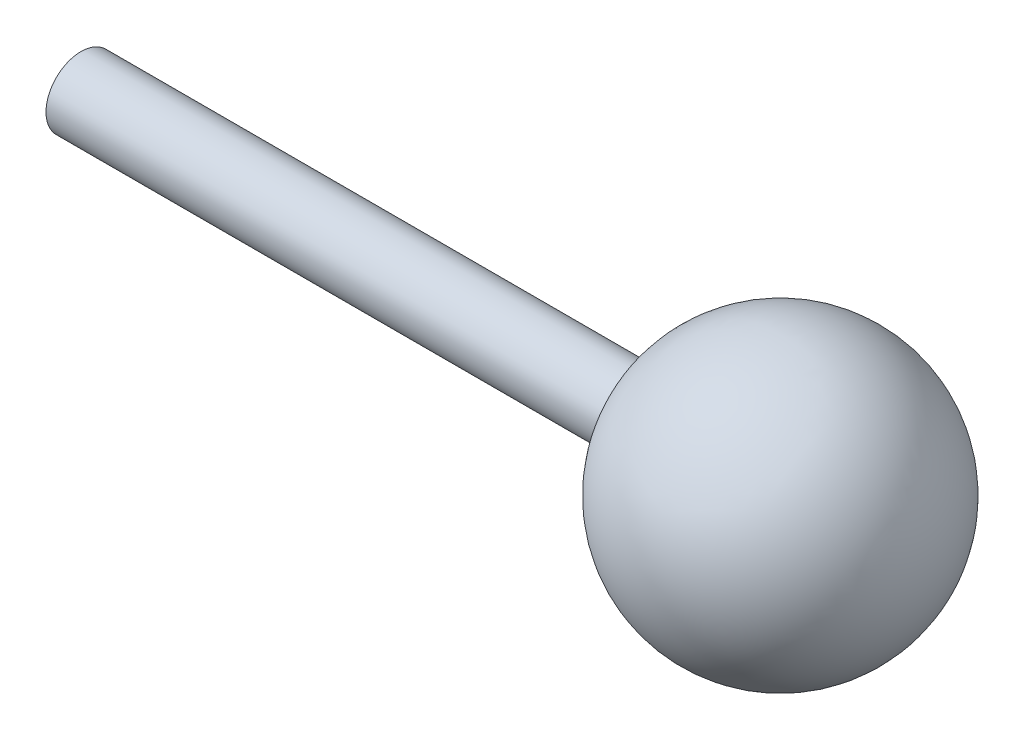
SolidWorks part; units mm, degrees
ref_plane "Front Plane" through (0, 0, 0) normal (0, 0, 1) x (1, 0, 0)
ref_plane "Top Plane" through (0, 0, 0) normal (0, 1, 0) x (1, 0, 0)
ref_plane "Right Plane" through (0, 0, 0) normal (1, 0, 0) x (0, 0, -1)
sketch "Sketch1" plane through (0, 0, 0) normal (0, 0, 1) x (1, 0, 0)
  line L0 (0, 0) -> (300, 0)
  line L1 (0, 0) -> (0, 12.5)
  line L2 (0, 12.5) -> (201.5877, 12.5)
  line L3 (-17.8024, 0) -> (114.9305, 0) construction
  arc A0 (201.5877, 12.5) -> (300, 0) centre (250, 0) cw
  circle A1 centre (250, 0) radius 50 construction
  dimension "D2" = 100
  dimension "D1" = 25
  dimension "D3" = 250
revolve "Revolve1" add sketch "Sketch1" angle 360 about L3
